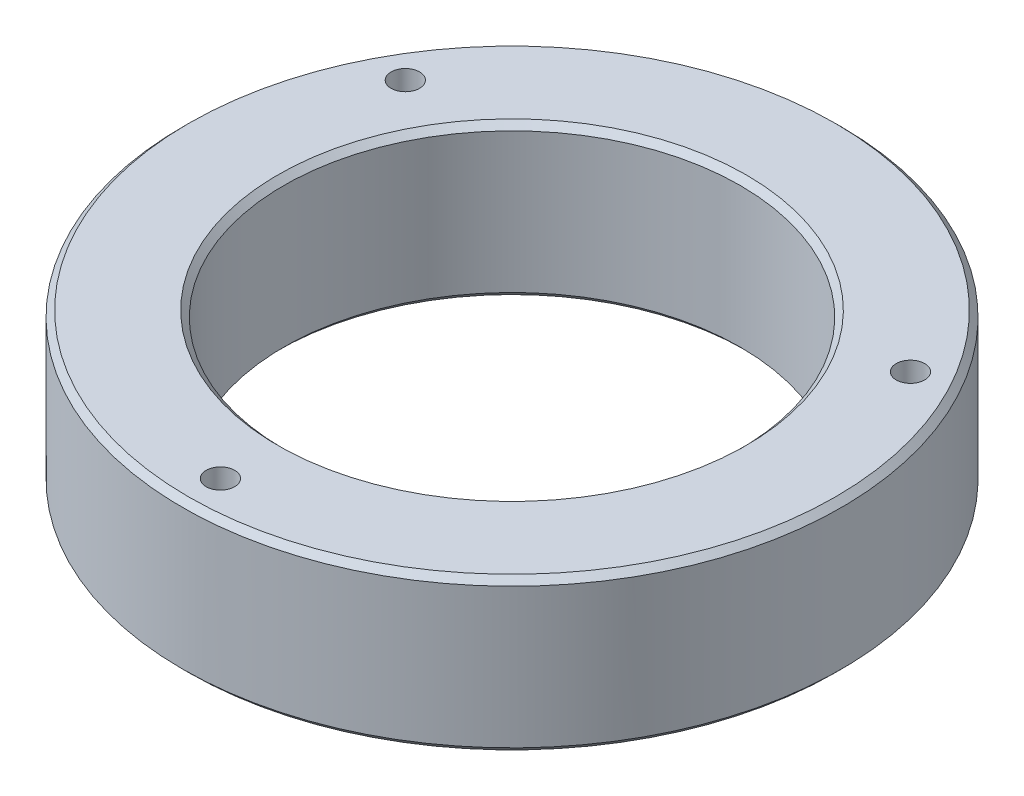
SolidWorks part; units mm, degrees
ref_plane "Front Plane" through (0, 0, 0) normal (1, 0, 0) x (0, 1, 0)
ref_plane "Top Plane" through (0, 0, 0) normal (0, 0, 1) x (0, 1, 0)
ref_plane "Right Plane" through (0, 0, 0) normal (0, 1, 0) x (-1, 0, 0)
sketch "Sketch1" plane through (0, 0, 0) normal (0, 0, 1) x (0, 1, 0)
  line L0 (-19.05, 82.5246) -> (19.05, 82.5246)
  line L1 (19.05, 82.5246) -> (19.05, 57.15)
  line L2 (19.05, 57.15) -> (-19.05, 57.15)
  line L3 (-19.05, 57.15) -> (-19.05, 82.5246)
  line L4 (-44.45, 0) -> (44.45, 0) construction
  point P6 (0, 0)
  dimension "D1" = 38.1
  dimension "D2" = 25.3746
  dimension "D3" = 82.5246
  dimension "D4" = 19.05
revolve "Revolve1" add sketch "Sketch1" angle 360 about L4
chamfer "Chamfer1" distance 1.524 angle 45 4 edges at (0, 19.05, -57.15) (0, -19.05, -57.15) (0, 19.05, -82.5246) (0, -19.05, -82.5246)
hole_wizard "CBORE for 1/4 Socket Head Cap Screw1" positions "Sketch3" profile "Sketch2" counterbore size "1/4" standard "ANSI Inch"
sketch "Sketch3" plane through (0, -19.05, 0) normal (0, -1, 0) x (-1, 0, 0)
  circle A0 centre (0, 0.0068) radius 73.0318 construction
  circle A1 centre (0, 0) radius 58.674 construction
  point P0 (0, -73.025)
  point P1 (-63.246, 36.5252)
  point P3 (63.246, 36.5252)
  dimension "D1" = 146.0637
  dimension "D2" = 63.246
  dimension "D3" = 63.246
  dimension "D4" = 0.0068
  dimension "D6" = 73.025
sketch "Sketch2" plane through (0, -19.05, 73.025) normal (1, 0, 0) x (0, 0, -1)
  line L0 (0, 0) -> (0, 40.2443)
  line L1 (0, 40.2443) -> (3.5687, 38.1)
  line L2 (3.5687, 38.1) -> (3.5687, 9.652)
  line L3 (3.5687, 9.652) -> (5.5626, 9.652)
  line L4 (5.5626, 9.652) -> (5.5626, 0)
  line L5 (5.5626, 0) -> (0, 0)
  line L10 (0, 40.2443) -> (-3.5687, 38.1) construction
  line L11 (0, -6.35) -> (0, 107.95) construction
  dimension "Hole Dia." = 7.1374
  dimension "Hole Depth" = 38.1
  dimension "C'Bore Dia." = 11.1252
  dimension "C'Bore Depth" = 9.652
  dimension "Drill Angle" = 118
hole_wizard "3/8-16 Tapped Hole2" positions "Sketch7" profile "Sketch6" tap size "3/8-16" standard "ANSI Inch"
sketch "Sketch7" plane through (0, -19.05, 0) normal (0, -1, 0) x (-1, 0, 0)
  circle A0 centre (0, -73.025) radius 5.5626 construction
  point P0 (-69.85, 0)
  point P1 (69.85, 0)
  dimension "D1" = 69.85
  dimension "D2" = 69.85
  dimension "D3" = 73.025
sketch "Sketch6" plane through (69.85, -19.05, 0) normal (1, 0, 0) x (0, 0, -1)
  line L0 (0, 0) -> (0, 27.7847)
  line L1 (0, 27.7847) -> (3.9687, 25.4)
  line L2 (3.9687, 25.4) -> (3.9687, 0)
  line L5 (3.9687, 0) -> (0, 0)
  line L10 (0, 27.7847) -> (-3.9687, 25.4) construction
  line L11 (0, -6.35) -> (0, 107.95) construction
  dimension "Tap Drill Dia." = 7.9375
  dimension "Tap Drill Depth" = 25.4
  dimension "Drill Angle" = 118
cosmetic thread "Hole Thread3" parameters "D1"=19.05, "D2"=9.525
cosmetic thread "Hole Thread4" parameters "D1"=19.05, "D2"=9.525
